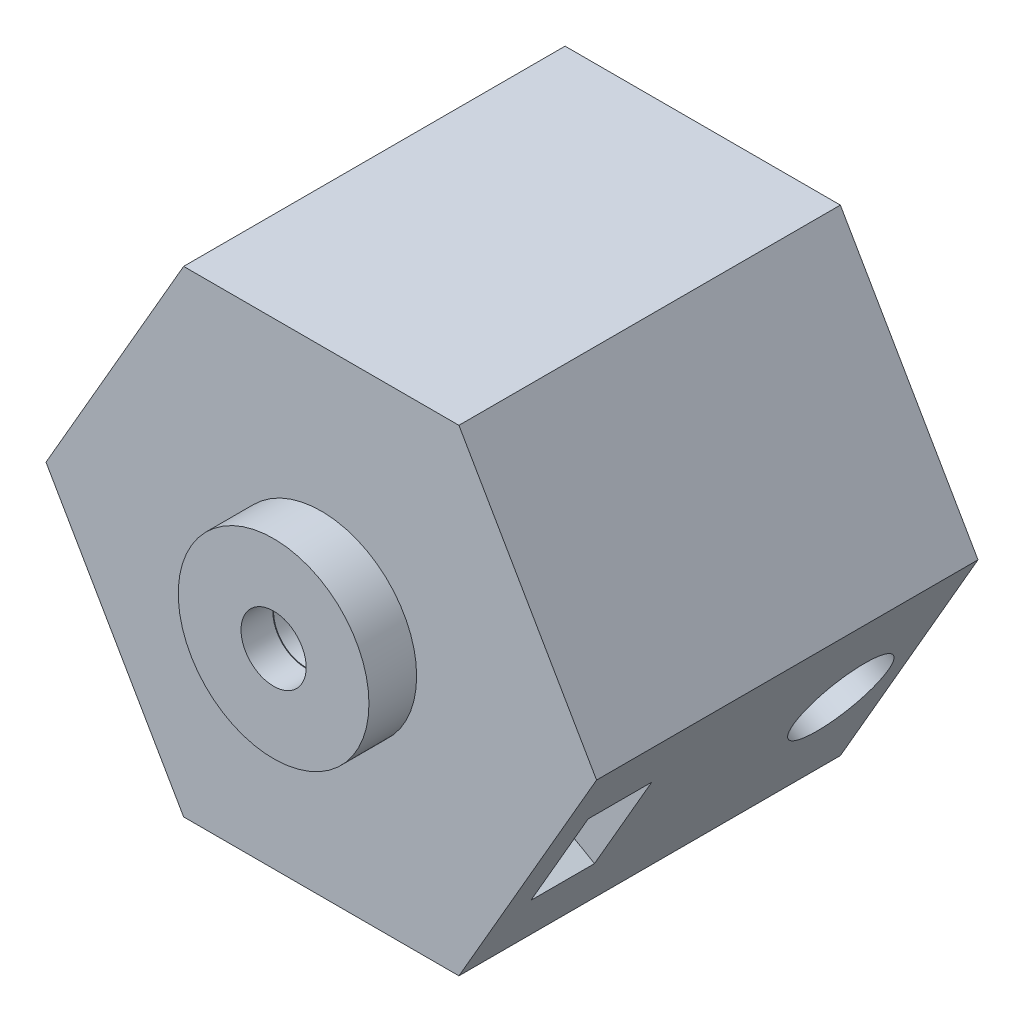
SolidWorks part; units mm, degrees
ref_plane "Alzado" through (0, 0, 0) normal (0, 0, 1) x (1, 0, 0)
ref_plane "Planta" through (0, 0, 0) normal (0, 1, 0) x (1, 0, 0)
ref_plane "Vista lateral" through (0, 0, 0) normal (1, 0, 0) x (0, 0, -1)
sketch "Croquis1" plane through (0, 0, 0) normal (0, 0, 1) x (1, 0, 0)
  line L1 (12.7017, 0) -> (6.3509, 11)
  line L2 (6.3509, 11) -> (-6.3509, 11)
  line L3 (-6.3509, 11) -> (-12.7017, 0)
  line L4 (-12.7017, 0) -> (-6.3509, -11)
  line L5 (-6.3509, -11) -> (6.3509, -11)
  line L6 (6.3509, -11) -> (12.7017, 0)
  line L7 (17.3205, 0) -> (8.6603, 15)
  line L8 (8.6603, 15) -> (-8.6603, 15)
  line L9 (-8.6603, 15) -> (-17.3205, 0)
  line L10 (-17.3205, 0) -> (-8.6603, -15)
  line L11 (-8.6603, -15) -> (8.6603, -15)
  line L12 (8.6603, -15) -> (17.3205, 0)
  circle A0 centre (0, 0) radius 11 construction
  circle A1 centre (0, 0) radius 15 construction
  dimension "D1" = 22
  dimension "D2" = 4
extrude "Saliente-Extruir1" add sketch "Croquis1" along normal blind 11
sketch "Croquis2" plane through (0, 0, 11) normal (0, 0, 1) x (1, 0, 0)
  line L1 (-8.6603, 15) -> (-17.3205, 0)
  line L2 (-17.3205, 0) -> (-8.6603, -15)
  line L3 (-8.6603, -15) -> (8.6603, -15)
  line L4 (8.6603, -15) -> (17.3205, 0)
  line L5 (17.3205, 0) -> (8.6603, 15)
  line L6 (8.6603, 15) -> (-8.6603, 15)
  circle A0 centre (0, 0) radius 15 construction
  circle A1 centre (0, 0) radius 2
  dimension "D1" = 4
extrude "Saliente-Extruir3" add sketch "Croquis2" along normal blind 16
sketch "Croquis3" plane through (0, 0, 27) normal (0, 0, 1) x (1, 0, 0)
  circle A0 centre (0, 0) radius 2.05
  dimension "D1" = 4.1
extrude "Cortar-Extruir1" cut sketch "Croquis3" against normal blind 2
sketch "Croquis4" plane through (0, 0, 11) normal (0, 0, -1) x (-1, 0, 0)
  circle A0 centre (0, 0) radius 3.5
  dimension "D1" = 7
extrude "Cortar-Extruir2" cut sketch "Croquis4" against normal blind 4
sketch "Croquis5" plane through (-12.9904, 7.5, 0) normal (-0.866, 0.5, 0) x (0, 0, 1)
  line L1 (18, 3.6) -> (22, 3.6)
  line L2 (18, 3.6) -> (18, -3.6)
  line L3 (18, -3.6) -> (22, -3.6)
  line L4 (22, 3.6) -> (22, -3.6)
  line L6 (15, 2) -> (15, -2) construction
  dimension "D1" = 7.2
  dimension "D2" = 3.6
  dimension "D3" = 4
  dimension "D4" = 3
extrude "Cortar-Extruir3" cut sketch "Croquis5" against normal through all
sketch "Croquis6" plane through (-12.9904, 7.5, 0) normal (-0.866, 0.5, 0) x (0, 0, 1)
  line L0 (0, 8.6603) -> (0, -8.6603) construction
  circle A0 centre (4.3, 0) radius 3
  point P2 (0, 0)
  dimension "D1" = 6
  dimension "D2" = 4.3
extrude "Cortar-Extruir4" cut sketch "Croquis6" against normal through all
sketch "Croquis7" plane through (0, 0, 27) normal (0, 0, 1) x (1, 0, 0)
  line L1 (-8.6603, 15) -> (-17.3205, 0)
  line L2 (-17.3205, 0) -> (-8.6603, -15)
  line L3 (-8.6603, -15) -> (8.6603, -15)
  line L4 (8.6603, -15) -> (17.3205, 0)
  line L5 (17.3205, 0) -> (8.6603, 15)
  line L6 (8.6603, 15) -> (-8.6603, 15)
  circle A0 centre (0, 0) radius 6
  circle A1 centre (0, 0) radius 15 construction
  dimension "D1" = 12
extrude "Cortar-Extruir5" cut sketch "Croquis7" against normal blind 3 contours L1 L2 L3 L4 L5 L6 | A0
